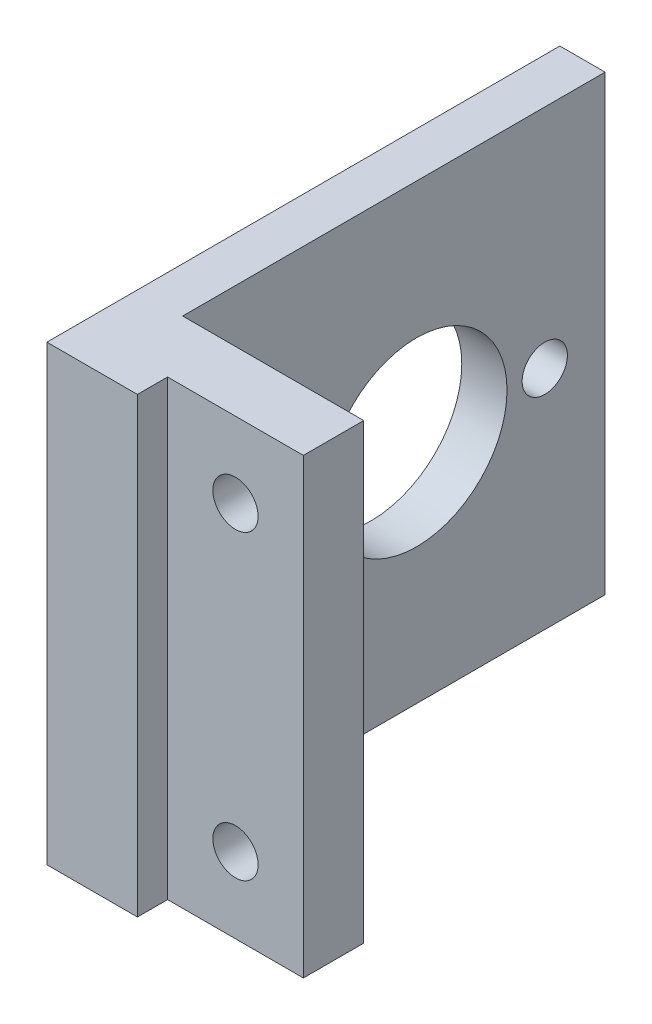
SolidWorks part; units mm, degrees
material "6061 合金"
ref_plane "前视基准面" through (0, 0, 0) normal (0, 0, 1) x (1, 0, 0)
ref_plane "上视基准面" through (0, 0, 0) normal (0, 1, 0) x (1, 0, 0)
ref_plane "右视基准面" through (0, 0, 0) normal (1, 0, 0) x (0, 0, -1)
sketch "草图1" plane through (0, 0, 0) normal (0, 1, 0) x (1, 0, 0)
  line L1 (0, 0) -> (15, 0)
  line L2 (0, 0) -> (0, 32)
  line L3 (0, 32) -> (3, 32)
  line L4 (15, 0) -> (15, 4)
  line L7 (15, 4) -> (3, 4)
  line L8 (3, 32) -> (3, 4)
  dimension "D1" = 28
  dimension "D2" = 3
  dimension "D3" = 4
  dimension "D4" = 15
extrude "凸台-拉伸1" add sketch "草图1" along normal blind 30
sketch "草图2" plane through (3, 0, 0) normal (1, 0, 0) x (0, 0, -1)
  line L0 (32, 15) -> (19.5, 15) construction
  line L1 (32, 30) -> (32, 0) construction
  circle A0 centre (19.5, 15) radius 6
  dimension "D1" = 12
  dimension "D2" = 12.5
extrude "切除-拉伸1" cut sketch "草图2" against normal blind 26
sketch "草图3" plane through (0, 0, 0) normal (0, 0, 1) x (1, 0, 0)
  line L0 (0, 0) -> (15, 0) construction
  line L1 (0, 30) -> (6, 30)
  line L2 (0, 30) -> (0, 0)
  line L3 (0, 0) -> (6, 0)
  line L4 (6, 30) -> (6, 0)
  line L5 (15, 30) -> (15, 0) construction
  dimension "D1" = 9
extrude "凸台-拉伸2" add sketch "草图3" along normal blind 2
sketch "草图4" plane through (3, 0, 0) normal (1, 0, 0) x (0, 0, -1)
  circle A0 centre (19.5, 15) radius 8.5 construction
  circle A1 centre (28, 15) radius 1.5
  circle A2 centre (11, 15) radius 1.5
  dimension "D1" = 17
  dimension "D2" = 3
extrude "切除-拉伸2" cut sketch "草图4" against normal through all
sketch "草图5" plane through (0, 0, 0) normal (0, 0, 1) x (1, 0, 0)
  line L0 (10.5, 30) -> (10.5, -5.9) construction
  line L1 (6, 30) -> (15, 30) construction
  line L2 (8.2708, 15) -> (15, 15) construction
  line L3 (15, 30) -> (15, 0) construction
  circle A0 centre (10.5, 25) radius 1.5
  circle A1 centre (10.5, 5) radius 1.5
  point P10 (15, 15)
  dimension "D1" = 20
  dimension "D2" = 3
extrude "切除-拉伸3" cut sketch "草图5" against normal through all
